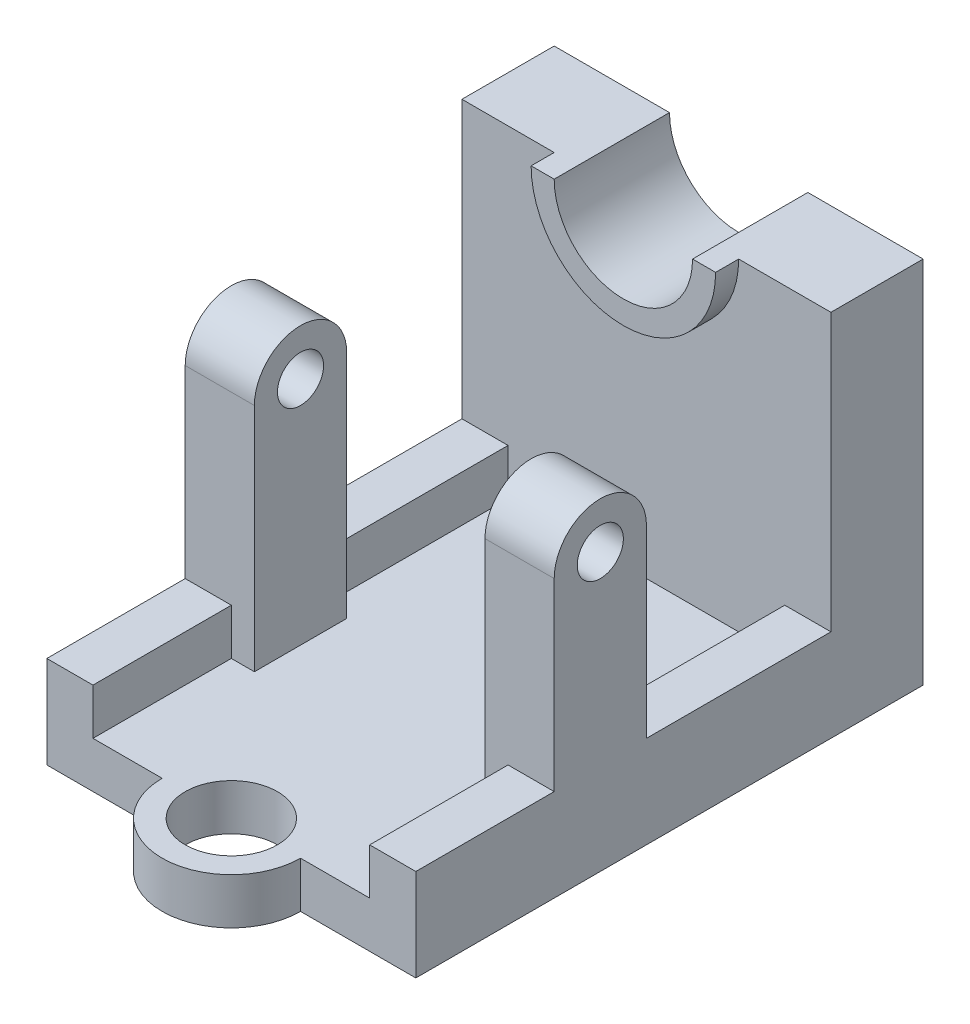
SolidWorks part; units mm, degrees
ref_plane "Front Plane" through (0, 0, 0) normal (0, 0, 1) x (1, 0, 0)
ref_plane "Top Plane" through (0, 0, 0) normal (0, 1, 0) x (1, 0, 0)
ref_plane "Right Plane" through (0, 0, 0) normal (1, 0, 0) x (0, 0, -1)
sketch "Sketch1" plane through (0, 0, 0) normal (0, 0, 1) x (1, 0, 0)
  line L0 (-40, 20) -> (-40, 0)
  line L1 (-40, 0) -> (40, 0)
  line L2 (-40, 20) -> (-30, 20)
  line L3 (-30, 20) -> (-30, 10)
  line L4 (-30, 10) -> (30, 10)
  line L5 (0, -55) -> (0, 55) construction
  line L6 (30, 20) -> (30, 10)
  line L7 (40, 20) -> (30, 20)
  line L8 (40, 20) -> (40, 0)
  point P10 (0, 10)
  point P13 (0, 0)
  dimension "D1" = 80
  dimension "D2" = 20
  dimension "D3" = 10
  dimension "D4" = 10
  dimension "D5" = 10
extrude "Boss-Extrude1" add sketch "Sketch1" along normal blind 110
sketch "Sketch2" plane through (0, 0, 0) normal (0, 0, -1) x (-1, 0, 0)
  line L5 (40, 20) -> (40, 0) construction
  line L10 (-40, 0) -> (40, 0)
  line L11 (-40, 0) -> (-40, 80)
  line L12 (-40, 80) -> (40, 80)
  line L13 (40, 0) -> (40, 80)
  dimension "D1" = 80
extrude "Boss-Extrude2" add sketch "Sketch2" against normal blind 20
sketch "Sketch3" plane through (0, 0, 20) normal (0, 0, 1) x (1, 0, 0)
  line L0 (-40, 80) -> (40, 80) construction
  circle A0 centre (0, 80) radius 15
  dimension "D1" = 30
extrude "Cut-Extrude1" cut sketch "Sketch3" against normal blind 20
sketch "Sketch4" plane through (0, 0, 20) normal (0, 0, 1) x (1, 0, 0)
  line L0 (-20, 80) -> (-15, 80)
  line L1 (15, 80) -> (20, 80)
  arc A0 (-15, 80) -> (15, 80) centre (0, 80) ccw
  arc A1 (-20, 80) -> (20, 80) centre (0, 80) ccw
  arc A2 (-15, 80) -> (15, 80) centre (0, 80) ccw construction
  dimension "D1" = 40
extrude "Boss-Extrude3" add sketch "Sketch4" along normal blind 5
sketch "Sketch6" plane through (0, 10, 0) normal (0, 1, 0) x (1, 0, 0)
  line L0 (30, -110) -> (-30, -110) construction
  line L1 (-15, -110) -> (15, -110)
  arc A0 (-15, -110) -> (15, -110) centre (0, -110) ccw
  dimension "D1" = 30
extrude "Boss-Extrude4" add sketch "Sketch6" against normal up to surface (10 mm away) up to face at (0, 0, 55)
hole_wizard "Hole1" positions "Sketch7" profile "Sketch8" legacy end condition up to next
sketch "Sketch7" plane through (0, 10, 0) normal (0, 1, 0) x (1, 0, 0)
  point P0 (0, -110)
sketch "Sketch8" plane through (0, 10, 110) normal (1, 0, 0) x (0, 0, 1)
  line L0 (0, 0) -> (0, 10)
  line L1 (0, 10) -> (10, 10)
  line L2 (10, 10) -> (10, 0)
  line L3 (10, 0) -> (0, 0)
  line L4 (0, 110) -> (0, -10) construction
  dimension "Diameter" = 20
  dimension "Depth" = 10
sketch "Sketch9" plane through (40, 0, 0) normal (1, 0, 0) x (0, 0, -1)
  line L0 (-125, 10) -> (-125, 0) construction
  line L1 (-80, 60) -> (-80, 0)
  line L2 (-110, 0) -> (0, 0) construction
  line L3 (-80, 0) -> (-60, 0)
  line L4 (-60, 0) -> (-60, 60)
  arc A0 (-60, 60) -> (-80, 60) centre (-70, 60) ccw
  circle A1 centre (-70, 60) radius 5
  dimension "D2" = 20
  dimension "D4" = 10
  dimension "D1" = 55
  dimension "D3" = 60
extrude "Boss-Extrude5" add sketch "Sketch9" against normal blind 15
pattern_linear "LPattern1" count 2 spacing 65 along (-1, 0, 0) of "Boss-Extrude5"
